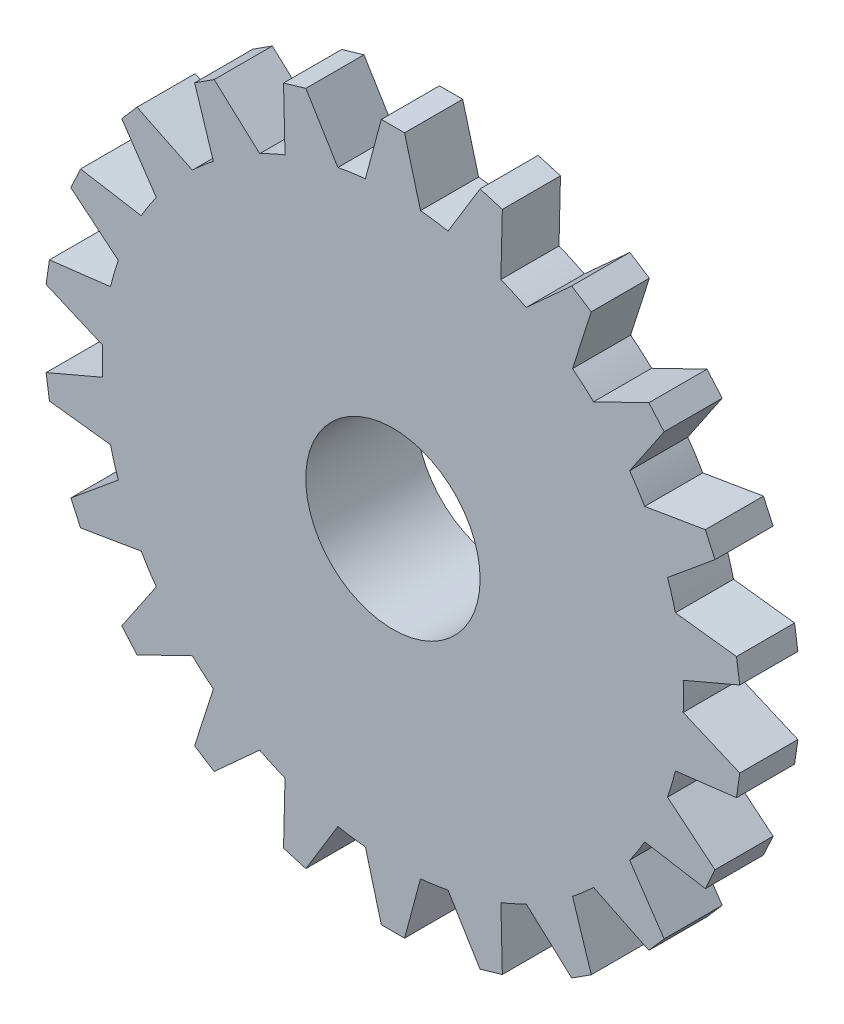
SolidWorks part; units mm, degrees
ref_plane "Front Plane" through (0, 0, 0) normal (0, 0, 1) x (1, 0, 0)
ref_plane "Top Plane" through (0, 0, 0) normal (0, 1, 0) x (1, 0, 0)
ref_plane "Right Plane" through (0, 0, 0) normal (1, 0, 0) x (0, 0, -1)
sketch "Sketch3" plane through (0, 0, 0) normal (0, 0, 1) x (1, 0, 0)
  circle A0 centre (0, 0) radius 12.7
extrude "Boss-Extrude2" add sketch "Sketch3" along normal blind 2.54
sketch "Sketch4" plane through (0, 0, 2.54) normal (0, 0, 1) x (1, 0, 0)
  line L0 (0, 0.4145) -> (0, 0) construction
  line L1 (0, 0) -> (0, 16.4746) construction
  line L2 (-0.508, 15.24) -> (0.508, 15.24)
  line L3 (0.508, 15.24) -> (1.6574, 10.9505)
  line L4 (1.6574, 10.9505) -> (-1.6574, 10.9505)
  line L5 (-1.6574, 10.9505) -> (-0.508, 15.24)
  dimension "D1" = 0.508
  dimension "D2" = 0.508
  dimension "D3" = 105
  dimension "D4" = 105
  dimension "D5" = 10.9505
  dimension "D6" = 15.24
extrude "Boss-Extrude4" add sketch "Sketch4" against normal blind 2.54
pattern_circular "CirPattern1" count 22 over 360 about axis through (0, 0, 0) along (0, 0, 1) of "Boss-Extrude4", "Boss-Extrude2"
sketch "Sketch5" plane through (0, 0, 0) normal (0, 0, -1) x (-1, 0, 0)
  circle A0 centre (0, 0) radius 11.43
  point P3 (-36.003, -11.2938)
extrude "Boss-Extrude6" add sketch "Sketch5" against normal blind 0.254
sketch "Sketch6" plane through (0, 0, 2.54) normal (0, 0, 1) x (1, 0, 0)
  circle A0 centre (0, 0) radius 3.81
extrude "Cut-Extrude1" cut sketch "Sketch6" against normal blind 16.08 contours A0
sketch "Sketch8" plane through (0, 0, 0) normal (0, 0, -1) x (-1, 0, 0)
  circle A0 centre (0, 0) radius 11.43
extrude "Cut-Extrude2" cut sketch "Sketch8" against normal blind 0.254
sketch "Sketch9" plane through (0, 0, 0.254) normal (0, 0, -1) x (-1, 0, 0)
  circle A0 centre (0, 0) radius 5.08
extrude "Boss-Extrude11" add sketch "Sketch9" along normal blind 2.54
sketch "Sketch10" plane through (0, 0, -2.286) normal (0, 0, -1) x (-1, 0, 0)
  circle A0 centre (0, 0) radius 3.81
extrude "Cut-Extrude3" cut sketch "Sketch10" against normal blind 2.54
